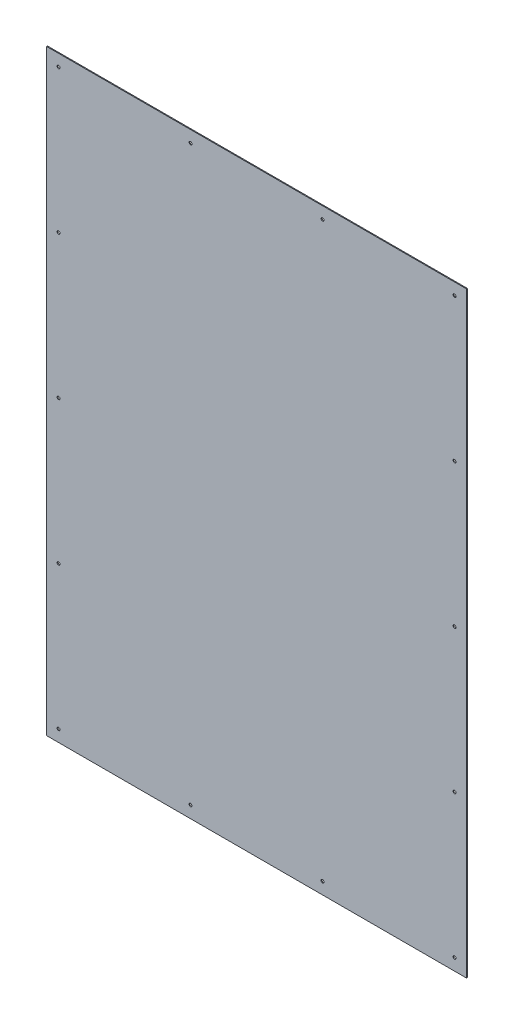
SolidWorks part; units mm, degrees
ref_plane "Alzado" through (0, 0, 0) normal (0, 0, 1) x (1, 0, 0)
ref_plane "Planta" through (0, 0, 0) normal (0, 1, 0) x (1, 0, 0)
ref_plane "Vista lateral" through (0, 0, 0) normal (1, 0, 0) x (0, 0, -1)
sketch "Croquis1" plane through (0, 0, 0) normal (0, 0, 1) x (1, 0, 0)
  line L1 (-450, 640) -> (450, 640)
  line L2 (-450, 640) -> (-450, -640)
  line L3 (-450, -640) -> (450, -640)
  line L4 (450, 640) -> (450, -640)
  line L5 (-450, 640) -> (450, -640) construction
  line L6 (-450, -640) -> (450, 640) construction
  point P0 (0, 0)
  dimension "D1" = 900
  dimension "D2" = 1280
extrude "Saliente-Extruir1" add sketch "Croquis1" along normal blind 1.9
sketch "Croquis2" plane through (0, 0, 1.9) normal (0, 0, 1) x (1, 0, 0)
  line L0 (450, 640) -> (-450, 640) construction
  line L1 (-424.6, -614.6) -> (424.6, -614.6) construction
  line L2 (-424.6, -614.6) -> (-424.6, 614.6) construction
  line L3 (-424.6, 614.6) -> (424.6, 614.6) construction
  line L4 (424.6, -614.6) -> (424.6, 614.6) construction
  line L5 (-424.6, -614.6) -> (424.6, 614.6) construction
  line L6 (-424.6, 614.6) -> (424.6, -614.6) construction
  line L7 (-450, 640) -> (-450, -640) construction
  line L8 (-424.6, 0) -> (-424.6, 614.6) construction
  line L9 (-424.6, 614.6) -> (-424.6, 307.3) construction
  line L10 (-424.6, 0) -> (-424.6, -614.6) construction
  line L11 (-424.6, 0) -> (-424.6, -614.6) construction
  line L12 (-424.6, -614.6) -> (-424.6, -307.3) construction
  line L13 (0, 0) -> (0, 254.0608) construction
  line L14 (-424.6, 0) -> (424.6, 0) construction
  circle A0 centre (-424.6, 0) radius 3.175
  circle A1 centre (-424.6, 614.6) radius 3.15
  circle A2 centre (424.6, 614.6) radius 3.175
  circle A3 centre (-141.54, 614.6) radius 3.15
  circle A4 centre (141.52, 614.6) radius 3.15
  circle A5 centre (-424.6, 307.3) radius 3.175
  circle A6 centre (-424.6, -307.3) radius 3.175
  circle A7 centre (424.6, -307.3) radius 3.175
  circle A8 centre (424.6, 0) radius 3.175
  circle A9 centre (424.6, 307.3) radius 3.175
  circle A10 centre (141.52, -614.6) radius 3.15
  circle A11 centre (-141.54, -614.6) radius 3.15
  circle A12 centre (424.6, -614.6) radius 3.175
  circle A13 centre (-424.6, -614.6) radius 3.15
  point P0 (0, 0)
  dimension "D3" = 6.35
  dimension "D4" = 6.3
  dimension "D5" = 6.35
  dimension "D7" = 6.35
  dimension "D8" = 6.35
  dimension "D1" = 25.4
  dimension "D2" = 25.4
  dimension "D9" = 283.06
  dimension "D6" = 3
extrude "Cortar-Extruir2" cut sketch "Croquis2" against normal blind 10
